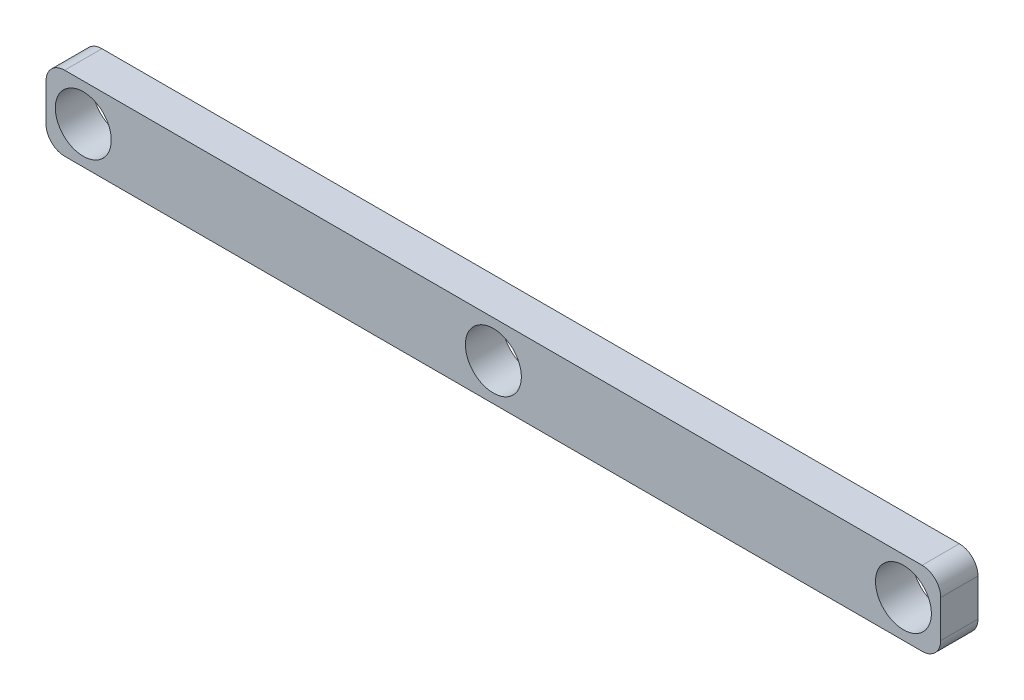
SolidWorks part; units mm, degrees
ref_plane "Front Plane" through (0, 0, 0) normal (0, 0, 1) x (1, 0, 0)
ref_plane "Top Plane" through (0, 0, 0) normal (0, 1, 0) x (1, 0, 0)
ref_plane "Right Plane" through (0, 0, 0) normal (1, 0, 0) x (0, 0, -1)
sketch "Sketch1" plane through (0, 0, 0) normal (0, 0, 1) x (1, 0, 0)
  line L1 (0, 0) -> (609.6, 0)
  line L2 (0, 0) -> (0, 50.8)
  line L3 (0, 50.8) -> (609.6, 50.8)
  line L4 (609.6, 0) -> (609.6, 50.8)
  dimension "D1" = 609.6
  dimension "D2" = 50.8
extrude "Boss-Extrude1" add sketch "Sketch1" along normal blind 25.4
sketch "Sketch2" plane through (0, 0, 25.4) normal (0, 0, 1) x (1, 0, 0)
  circle A0 centre (25.4, 25.4) radius 19.05
  dimension "D1" = 38.1
fillet "Fillet1" radius 12.7 4 edges at (0, 0, 12.7) (0, 50.8, 12.7) (609.6, 50.8, 12.7) (609.6, 0, 12.7)
sketch "Sketch4" plane through (0, 0, 25.4) normal (0, 0, 1) x (1, 0, 0)
  line L0 (596.9, 50.8) -> (12.7, 50.8) construction
  line L1 (609.6, 12.7) -> (609.6, 38.1) construction
  circle A0 centre (584.2, 25.4) radius 19.05
  dimension "D1" = 25.4
  dimension "D2" = 25.4
extrude "Cut-Extrude1" cut sketch "Sketch4" against normal through all
sketch "Sketch5" plane through (0, 0, 0) normal (0, 0, -1) x (-1, 0, 0)
  line L0 (-609.6, 25.4) -> (0, 25.4) construction
  line L1 (-609.6, 12.7) -> (-609.6, 38.1) construction
  line L2 (0, 38.1) -> (0, 12.7) construction
  circle A0 centre (-304.8, 25.4) radius 19.05
extrude "Cut-Extrude2" cut sketch "Sketch5" against normal through all
extrude "Cut-Extrude3" cut sketch "Sketch2" against normal through all
